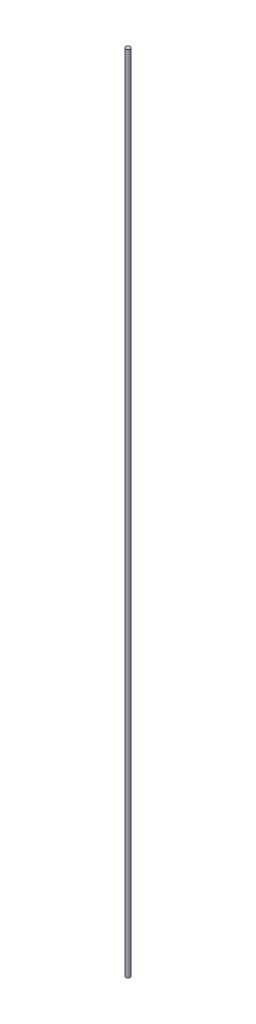
SolidWorks part; units mm, degrees
ref_plane "Front Plane" through (0, 0, 0) normal (0, 0, 1) x (1, 0, 0)
ref_plane "Top Plane" through (0, 0, 0) normal (0, 1, 0) x (1, 0, 0)
ref_plane "Right Plane" through (0, 0, 0) normal (1, 0, 0) x (0, 0, -1)
sketch "Sketch1" plane through (0, 0, 0) normal (0, 1, 0) x (1, 0, 0)
  circle A0 centre (0, 0) radius 4
  dimension "D1" = 8
extrude "Boss-Extrude1" add sketch "Sketch1" along normal blind 1500
